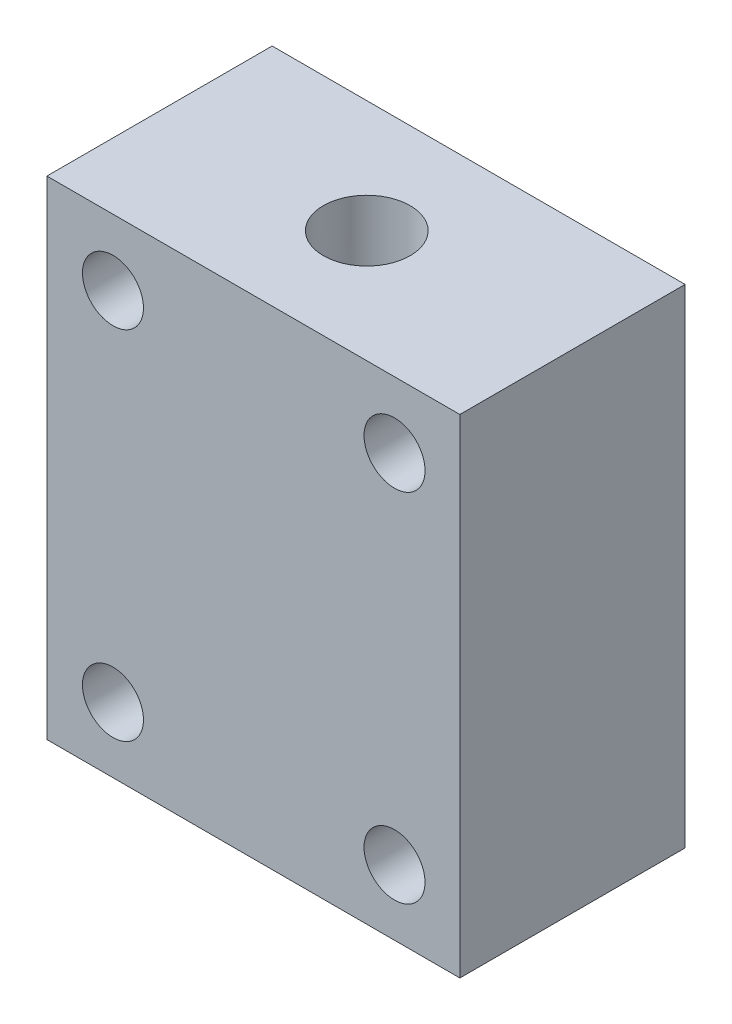
SolidWorks part; units mm, degrees
ref_plane "Front Plane" through (0, 0, 0) normal (1, 0, 0) x (0, 1, 0)
ref_plane "Top Plane" through (0, 0, 0) normal (0, 0, 1) x (0, 1, 0)
ref_plane "Right Plane" through (0, 0, 0) normal (0, 1, 0) x (-1, 0, 0)
sketch "Sketch1" plane through (0, 0, 0) normal (0, 0, 1) x (0, 1, 0)
  line L1 (-41.275, -34.925) -> (41.275, -34.925)
  line L2 (-41.275, -34.925) -> (-41.275, 34.925)
  line L3 (-41.275, 34.925) -> (41.275, 34.925)
  line L4 (41.275, -34.925) -> (41.275, 34.925)
  line L5 (-41.275, -34.925) -> (41.275, 34.925) construction
  line L6 (-41.275, 34.925) -> (41.275, -34.925) construction
  point P0 (0, 0)
extrude "Boss-Extrude1" add sketch "Sketch1" along normal mid plane 38.1
hole_wizard "3/8 Clearance Hole1" positions "Sketch3" profile "Sketch2" hole size "3/8" standard "ANSI Inch"
sketch "Sketch3" plane through (0, 0, -19.05) normal (0, 0, -1) x (-1, 0, 0)
  point P0 (-23.876, -30.226)
sketch "Sketch2" plane through (23.876, -30.226, -19.05) normal (1, 0, 0) x (0, 1, 0)
  line L0 (0, 0) -> (0, 41.2001)
  line L1 (0, 41.2001) -> (5.1594, 38.1)
  line L2 (5.1594, 38.1) -> (5.1594, 0)
  line L5 (5.1594, 0) -> (0, 0)
  line L10 (0, 41.2001) -> (-5.1594, 38.1) construction
  line L11 (0, -6.35) -> (0, 107.95) construction
  dimension "Hole Dia." = 10.3187
  dimension "Hole Depth" = 38.1
  dimension "Drill Angle" = 118
hole_wizard "3/8 Clearance Hole2" positions "Sketch5" profile "Sketch4" hole size "3/8" standard "ANSI Inch"
sketch "Sketch5" plane through (0, 0, -19.05) normal (0, 0, -1) x (-1, 0, 0)
  point P0 (-23.876, 30.099)
  point P1 (23.749, -30.226)
  point P3 (23.749, 30.099)
sketch "Sketch4" plane through (23.876, 30.099, -19.05) normal (1, 0, 0) x (0, 1, 0)
  line L0 (0, 0) -> (0, 41.2001)
  line L1 (0, 41.2001) -> (5.1594, 38.1)
  line L2 (5.1594, 38.1) -> (5.1594, 0)
  line L5 (5.1594, 0) -> (0, 0)
  line L10 (0, 41.2001) -> (-5.1594, 38.1) construction
  line L11 (0, -6.35) -> (0, 107.95) construction
  dimension "Hole Dia." = 10.3187
  dimension "Hole Depth" = 38.1
  dimension "Drill Angle" = 118
sketch "Sketch6" plane through (0, 0, 0) normal (0, 0, 1) x (0, 1, 0)
  circle A0 centre (-17.653, -0.127) radius 7.3422
extrude "Cut-Extrude2" cut sketch "Sketch6" along normal blind 28.448 from offset 19.05
sketch "Sketch7" plane through (0, 0, 0) normal (0, 0, 1) x (0, 1, 0)
  circle A0 centre (-17.653, -0.127) radius 12.7254
extrude "Cut-Extrude4" cut sketch "Sketch7" along normal blind 2.8194 from offset 19.05
sketch "Sketch8" plane through (0, 0, 0) normal (0, 0, 1) x (0, 1, 0)
  circle A0 centre (17.399, -0.127) radius 7.3422
extrude "Cut-Extrude6" cut sketch "Sketch8" along normal blind 28.448 from offset 19.05
sketch "Sketch9" plane through (0, 0, 0) normal (0, 0, 1) x (0, 1, 0)
  circle A0 centre (17.399, -0.127) radius 12.7254
extrude "Cut-Extrude8" cut sketch "Sketch9" along normal blind 2.8194 from offset 19.05
sketch "Sketch10" plane through (0, 0, 0) normal (0, 1, 0) x (-1, 0, 0)
  circle A0 centre (-0.127, 0) radius 7.3422
extrude "Cut-Extrude10" cut sketch "Sketch10" against normal blind 60.452 from offset 41.275
